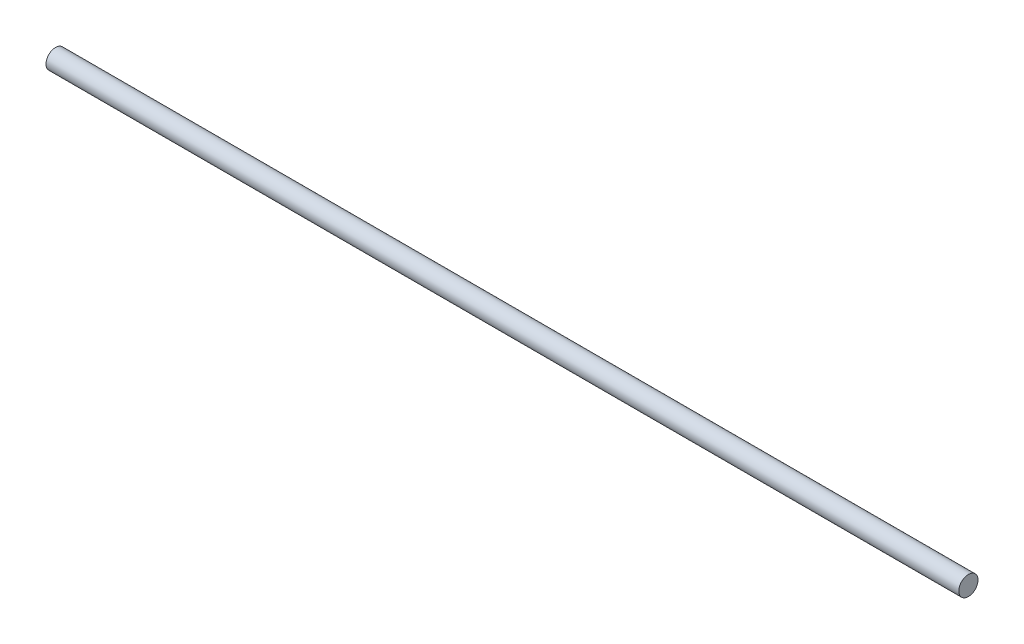
SolidWorks part; units mm, degrees
material "Plain Carbon Steel"
ref_plane "Front Plane" through (0, 0, 0) normal (0, 0, 1) x (1, 0, 0)
ref_plane "Top Plane" through (0, 0, 0) normal (0, 1, 0) x (1, 0, 0)
ref_plane "Right Plane" through (0, 0, 0) normal (1, 0, 0) x (0, 0, -1)
sketch "Sketch1" plane through (0, 0, 0) normal (1, 0, 0) x (0, 0, -1)
  circle A0 centre (0, 0) radius 2
  dimension "D1" = 4
extrude "Boss-Extrude1" add sketch "Sketch1" along normal mid plane 190
